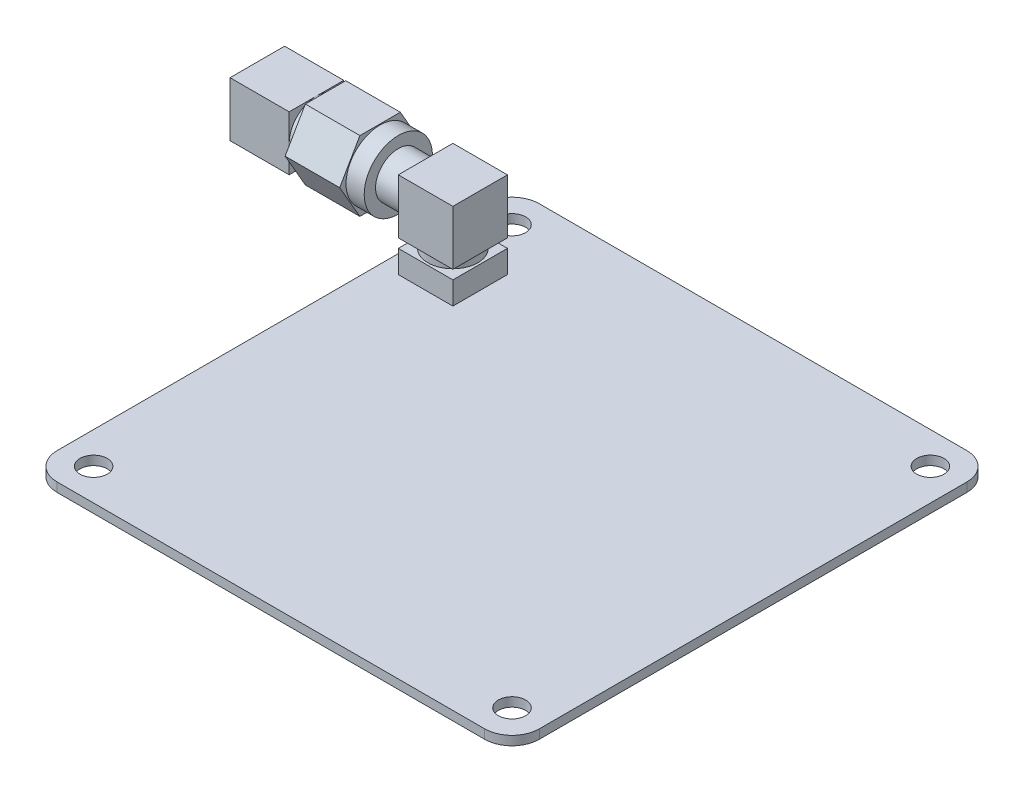
SolidWorks part; units mm, degrees
material "黄铜"
ref_plane "前视基准面" through (0, 0, 0) normal (0, 0, 1) x (1, 0, 0)
ref_plane "上视基准面" through (0, 0, 0) normal (0, 1, 0) x (1, 0, 0)
ref_plane "右视基准面" through (0, 0, 0) normal (1, 0, 0) x (0, 0, -1)
other "Configuration Table"
sketch "草图1" plane through (0, 0, 0) normal (0, 1, 0) x (1, 0, 0)
  line L1 (-26.5, -26.5) -> (26.5, -26.5)
  line L2 (-26.5, -26.5) -> (-26.5, 26.5)
  line L3 (-26.5, 26.5) -> (26.5, 26.5)
  line L4 (26.5, -26.5) -> (26.5, 26.5)
  line L5 (-26.5, -26.5) -> (26.5, 26.5) construction
  line L6 (-26.5, 26.5) -> (26.5, -26.5) construction
  point P0 (0, 0)
  dimension "D1" = 53
  dimension "D2" = 53
extrude "凸台-拉伸1" add sketch "草图1" along normal blind 1
sketch "草图2" plane through (0, 1, 0) normal (0, 1, 0) x (1, 0, 0)
  line L0 (26.5, 26.5) -> (-26.5, 26.5) construction
  line L1 (-24.5, 12) -> (-18.5, 12)
  line L2 (-24.5, 12) -> (-24.5, 18)
  line L3 (-24.5, 18) -> (-18.5, 18)
  line L4 (-18.5, 12) -> (-18.5, 18)
  line L5 (-24.5, 12) -> (-18.5, 18) construction
  line L6 (-24.5, 18) -> (-18.5, 12) construction
  line L7 (-26.5, 26.5) -> (-26.5, -26.5) construction
  point P4 (-21.5, 15)
  dimension "D1" = 8.5
  dimension "D2" = 2
  dimension "D3" = 6
  dimension "D4" = 6
extrude "凸台-拉伸2" add sketch "草图2" along normal blind 2.5
sketch "草图3" plane through (0, 3.5, 0) normal (0, 1, 0) x (1, 0, 0)
  line L0 (-24.5, 15) -> (-18.5, 15) construction
  line L1 (-24.5, 18) -> (-24.5, 12) construction
  line L2 (-18.5, 12) -> (-18.5, 18) construction
  line L3 (-21.5, 18) -> (-21.5, 12) construction
  line L4 (-18.5, 18) -> (-24.5, 18) construction
  line L5 (-24.5, 12) -> (-18.5, 12) construction
  circle A0 centre (-21.5, 15) radius 2.75
  dimension "D1" = 5.5
extrude "凸台-拉伸3" add sketch "草图3" along normal blind 1
sketch "草图4" plane through (0, 4.5, 0) normal (0, 1, 0) x (1, 0, 0)
  line L4 (-24.5, 18) -> (-24.5, 12)
  line L5 (-24.5, 12) -> (-18.5, 12)
  line L6 (-18.5, 12) -> (-18.5, 18)
  line L7 (-18.5, 18) -> (-24.5, 18)
  line L8 (-24.5, 18) -> (-24.5, 12)
  line L9 (-24.5, 12) -> (-18.5, 12)
  line L10 (-18.5, 12) -> (-18.5, 18)
  line L11 (-18.5, 18) -> (-24.5, 18)
  dimension "D1" = 0
extrude "凸台-拉伸4" add sketch "草图4" along normal blind 6
sketch "草图5" plane through (-24.5, 0, 0) normal (-1, 0, 0) x (0, 0, 1)
  line L0 (-18, 7.5) -> (-12, 7.5) construction
  line L1 (-18, 10.5) -> (-18, 4.5) construction
  line L2 (-12, 10.5) -> (-12, 4.5) construction
  line L3 (-15, 10.5) -> (-15, 4.5) construction
  line L4 (-18, 10.5) -> (-12, 10.5) construction
  line L5 (-17.75, 4.5) -> (-12.25, 4.5) construction
  circle A0 centre (-15, 7.5) radius 2.5
  dimension "D1" = 5
extrude "凸台-拉伸5" add sketch "草图5" along normal blind 3
sketch "草图6" plane through (-27.5, 0, 0) normal (-1, 0, 0) x (0, 0, 1)
  circle A0 centre (-15, 7.5) radius 3.75
  dimension "D1" = 7.5
extrude "凸台-拉伸6" add sketch "草图6" along normal blind 2
sketch "草图7" plane through (-29.5, 0, 0) normal (-1, 0, 0) x (0, 0, 1)
  line L1 (-10.5544, 7.5) -> (-12.7772, 11.35)
  line L2 (-12.7772, 11.35) -> (-17.2228, 11.35)
  line L3 (-17.2228, 11.35) -> (-19.4456, 7.5)
  line L4 (-19.4456, 7.5) -> (-17.2228, 3.65)
  line L5 (-17.2228, 3.65) -> (-12.7772, 3.65)
  line L6 (-12.7772, 3.65) -> (-10.5544, 7.5)
  circle A0 centre (-15, 7.5) radius 3.85 construction
  circle A3 centre (-15, 7.5) radius 3.75 construction
  dimension "D1" = 0.1
extrude "凸台-拉伸7" add sketch "草图7" along normal blind 6
sketch "草图8" plane through (-35.5, 0, 0) normal (-1, 0, 0) x (0, 0, 1)
  line L0 (-17.2228, 11.35) -> (-12.7772, 3.65) construction
  line L1 (-12.7772, 3.65) -> (-10.5544, 7.5) construction
  line L2 (-17.2228, 3.65) -> (-12.7772, 3.65) construction
  line L3 (-12.7772, 3.65) -> (-12.7772, 11.35) construction
  line L4 (-10.5544, 7.5) -> (-12.7772, 11.35) construction
  line L5 (-12.7772, 11.35) -> (-17.2228, 11.35) construction
  line L6 (-12.7772, 11.35) -> (-17.2228, 3.65) construction
  circle A0 centre (-15, 7.5) radius 3
  dimension "D1" = 6
extrude "凸台-拉伸8" add sketch "草图8" along normal blind 1
sketch "草图9" plane through (-36.5, 0, 0) normal (-1, 0, 0) x (0, 0, 1)
  line L1 (-18, 4.5) -> (-12, 4.5)
  line L2 (-18, 4.5) -> (-18, 10.5)
  line L3 (-18, 10.5) -> (-12, 10.5)
  line L4 (-12, 4.5) -> (-12, 10.5)
  line L5 (-18, 4.5) -> (-12, 10.5) construction
  line L6 (-18, 10.5) -> (-12, 4.5) construction
  point P0 (-15, 7.5)
extrude "凸台-拉伸9" add sketch "草图9" along normal blind 6.5
sketch "草图11" plane through (0, 1, 0) normal (0, 1, 0) x (1, 0, 0)
  line L0 (-26.5, -26.5) -> (26.5, -26.5) construction
  line L1 (-26.5, 26.5) -> (-26.5, -26.5) construction
  line L2 (26.5, 26.5) -> (-26.5, 26.5) construction
  line L3 (26.5, -26.5) -> (26.5, 26.5) construction
  circle A0 centre (-23, -23) radius 1.5
  circle A1 centre (-23, 23) radius 1.5
  circle A2 centre (23, 23) radius 1.5
  circle A3 centre (23, -23) radius 1.5
  dimension "D1" = 3
  dimension "D2" = 2
  dimension "D4" = 3
  dimension "D6" = 2
  dimension "D7" = 3
  dimension "D8" = 2
  dimension "D10" = 3
  dimension "D12" = 2
  dimension "D3" = 2
  dimension "D5" = 2
  dimension "D9" = 2
  dimension "D11" = 2
extrude "切除-拉伸1" cut sketch "草图11" against normal through all
fillet "圆角1" radius 3 4 edges at (-26.5, 0.5, 26.5) (26.5, 0.5, 26.5) (26.5, 0.5, -26.5) (-26.5, 0.5, -26.5)
